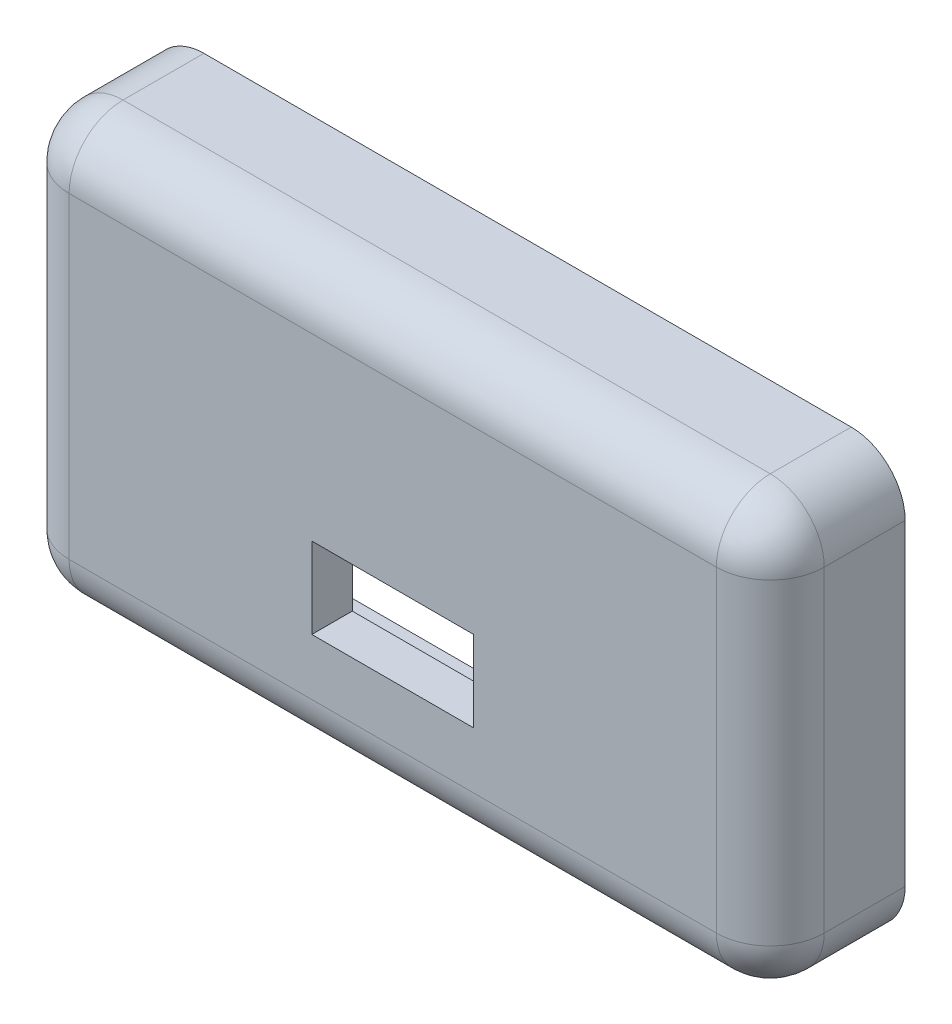
SolidWorks part; units mm, degrees
ref_plane "Přední rovina" through (0, 0, 0) normal (0, 0, 1) x (1, 0, 0)
ref_plane "Horní rovina" through (0, 0, 0) normal (0, 1, 0) x (1, 0, 0)
ref_plane "Pravá rovina" through (0, 0, 0) normal (1, 0, 0) x (0, 0, -1)
sketch "Sketch1" plane through (0, 0, 0) normal (0, 0, 1) x (1, 0, 0)
  line L1 (-14, 7.875) -> (14, 7.875)
  line L2 (-14, 7.875) -> (-14, -7.875)
  line L3 (-14, -7.875) -> (14, -7.875)
  line L4 (14, 7.875) -> (14, -7.875)
  line L5 (-14, 7.875) -> (14, -7.875) construction
  line L6 (-14, -7.875) -> (14, 7.875) construction
  line L7 (-3, -0.785) -> (3, -0.785)
  line L8 (-3, -0.785) -> (-3, -3.785)
  line L9 (-3, -3.785) -> (3, -3.785)
  line L10 (3, -0.785) -> (3, -3.785)
  line L11 (-3, -0.785) -> (3, -3.785) construction
  line L12 (-3, -3.785) -> (3, -0.785) construction
  point P0 (0, 0)
  point P6 (0, -2.285)
  dimension "D1" = 28
  dimension "D2" = 15.75
  dimension "D3" = 6
  dimension "D4" = 3
  dimension "D5" = 5.59
extrude "Boss-Extrude1" add sketch "Sketch1" along normal blind 1
sketch "Sketch2" plane through (0, 0, 1) normal (0, 0, 1) x (1, 0, 0)
  line L0 (-10, 0) -> (10, 0) construction
  circle A0 centre (10, 0) radius 1.475
  circle A1 centre (-10, 0) radius 1.475
  dimension "D1" = 2.95
  dimension "D2" = 2.95
  dimension "D3" = 20
extrude "Cut-Extrude1" cut sketch "Sketch2" against normal up to next
sketch "Sketch5" plane through (0, 0, 1) normal (0, 0, 1) x (1, 0, 0)
  line L0 (3, -3.785) -> (3, -0.785) construction
  line L1 (-3, -3.785) -> (3, -3.785) construction
  line L2 (-3, -0.785) -> (-3, -3.785) construction
  line L3 (3, -0.785) -> (-3, -0.785) construction
  line L4 (14, -7.875) -> (14, 7.875)
  line L5 (14, 7.875) -> (-14, 7.875)
  line L6 (-14, 7.875) -> (-14, -7.875)
  line L7 (-14, -7.875) -> (14, -7.875)
  line L8 (14, -7.875) -> (14, 7.875)
  line L9 (14, 7.875) -> (-14, 7.875)
  line L10 (-14, 7.875) -> (-14, -7.875)
  line L11 (-14, -7.875) -> (14, -7.875)
  line L12 (3, -3.785) -> (3, -0.785)
  line L13 (-3, -3.785) -> (3, -3.785)
  line L14 (-3, -0.785) -> (-3, -3.785)
  line L15 (3, -0.785) -> (-3, -0.785)
  dimension "D1" = 0
extrude "Boss-Extrude4" add sketch "Sketch5" along normal blind 0.5
sketch "Sketch3" plane through (0, 0, 0) normal (0, 0, -1) x (-1, 0, 0)
  circle A0 centre (-10, 0) radius 1.475
  circle A1 centre (10, 0) radius 1.475
  circle A2 centre (-10, 0) radius 1.475 construction
  circle A3 centre (10, 0) radius 1.475 construction
  circle A4 centre (-10, 0) radius 2.475
  circle A5 centre (10, 0) radius 2.475
  dimension "D1" = 1
  dimension "D2" = 1
extrude "Boss-Extrude2" add sketch "Sketch3" along normal blind 1
sketch "Sketch4" plane through (0, 0, 0) normal (0, 0, -1) x (-1, 0, 0)
  line L1 (-13, -6.875) -> (13, -6.875)
  line L2 (-13, -6.875) -> (-13, 6.875)
  line L3 (-13, 6.875) -> (13, 6.875)
  line L4 (-14, 7.875) -> (-14, -7.875)
  line L5 (-14, -7.875) -> (14, -7.875)
  line L6 (14, -7.875) -> (14, 7.875)
  line L7 (14, 7.875) -> (-14, 7.875)
  line L8 (-14, 7.875) -> (-14, -7.875)
  line L9 (-14, -7.875) -> (14, -7.875)
  line L10 (14, -7.875) -> (14, 7.875)
  line L11 (14, 7.875) -> (-14, 7.875)
  line L12 (13, -6.875) -> (13, 6.875)
  line L13 (-13, -6.875) -> (13, 6.875) construction
  line L14 (-13, 6.875) -> (13, -6.875) construction
  point P2 (0, 0)
  dimension "D2" = 1
  dimension "D3" = 1
  dimension "D1" = 0
extrude "Boss-Extrude3" add sketch "Sketch4" along normal blind 3.5
fillet "Fillet1" radius 2 8 edges at (14, 7.875, -1) (14, -7.875, -1) (-14, -7.875, -1) (-14, 7.875, -1) (0, -7.875, 1.5) (14, 0, 1.5) (0, 7.875, 1.5) (-14, 0, 1.5)
